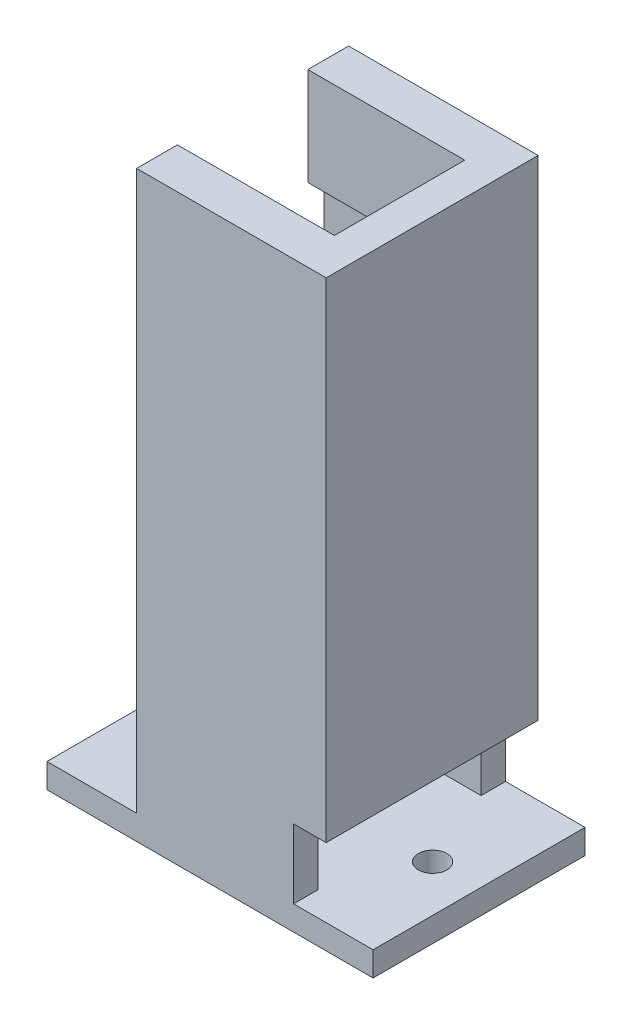
SolidWorks part; units mm, degrees
ref_plane "Front Plane" through (0, 0, 0) normal (0, 0, 1) x (1, 0, 0)
ref_plane "Top Plane" through (0, 0, 0) normal (0, 1, 0) x (1, 0, 0)
ref_plane "Right Plane" through (0, 0, 0) normal (1, 0, 0) x (0, 0, -1)
sketch "Sketch1" plane through (0, 0, 0) normal (0, 1, 0) x (1, 0, 0)
  line L1 (-20, 13) -> (20, 13)
  line L2 (-20, 13) -> (-20, -13)
  line L3 (-20, -13) -> (20, -13)
  line L4 (20, 13) -> (20, -13)
  dimension "D1" = 40
  dimension "D2" = 26
  dimension "D3" = 13
  dimension "D4" = 20
extrude "Boss-Extrude1" add sketch "Sketch1" along normal blind 3 contours L1 L4 L3 L2
sketch "Sketch2" plane through (0, 3, 0) normal (0, 1, 0) x (1, 0, 0)
  line L0 (20, 0) -> (14.3, 0) construction
  line L1 (20, 13) -> (20, -13) construction
  line L2 (0, 13) -> (0, -13) construction
  line L3 (-20, 13) -> (20, 13) construction
  line L4 (-20, -13) -> (20, -13) construction
  line L5 (-20, 0) -> (-14.3, 0) construction
  circle A0 centre (14.3, 0) radius 1.75
  circle A1 centre (-14.3, 0) radius 1.75
extrude "Cut-Extrude1" cut sketch "Sketch2" against normal blind 3
sketch "Sketch3" plane through (0, 3, 0) normal (0, 1, 0) x (1, 0, 0)
  line L0 (-20, 13) -> (20, 13) construction
  line L1 (0, 0) -> (50000, 0) construction
  line L2 (0, 0) -> (0, 50000) construction
  line L3 (-9, -10) -> (10.25, -10)
  line L4 (-9, 13) -> (10.25, 13)
  line L5 (-9, 13) -> (-9, 10)
  line L6 (-9, 10) -> (10.25, 10)
  line L7 (10.25, 13) -> (10.25, 10)
  line L8 (10.25, -13) -> (10.25, -10)
  line L9 (-9, -13) -> (10.25, -13)
  line L10 (-9, -13) -> (-9, -10)
  line L11 (0, 0) -> (10.5, 0) construction
  point P0 (-9, 13)
  point P9 (9, 13)
  dimension "D1" = 11
  dimension "D2" = 3
  dimension "D3" = 19.25
extrude "Boss-Extrude2" add sketch "Sketch3" along normal blind 56.5
sketch "Sketch5" plane through (0, 59.5, 0) normal (0, 1, 0) x (1, 0, 0)
  line L0 (-9, 13) -> (-9, -13) construction
  line L1 (-9, -8) -> (-9, 8) construction
  line L2 (-9, 0) -> (49991, 0) construction
  line L3 (-9, 13) -> (10.25, 13)
  line L4 (-9, 13) -> (-9, 8)
  line L5 (-9, 8) -> (10.25, 8)
  line L6 (10.25, 13) -> (10.25, 8)
  line L11 (-9, -8) -> (10.25, -8)
  line L12 (10.25, -13) -> (10.25, -8)
  line L13 (-9, -13) -> (10.25, -13)
  line L14 (-9, -13) -> (-9, -8)
  point P7 (-9, 0)
  dimension "D1" = 26
  dimension "D2" = 19.25
extrude "Boss-Extrude4" add sketch "Sketch5" along normal blind 12
sketch "Sketch6" plane through (0, 3, 0) normal (0, 1, 0) x (1, 0, 0)
  circle A0 centre (0, 0) radius 2.5
extrude "Cut-Extrude2" cut sketch "Sketch6" against normal blind 15
sketch "Sketch7" plane through (10.25, 0, 0) normal (1, 0, 0) x (0, 0, -1)
  line L0 (-13, 3) -> (-13, 11.5) construction
  line L1 (-13, 71.5) -> (-13, 3) construction
  line L3 (-13, 11.5) -> (13, 11.5)
  line L4 (-13, 11.5) -> (-13, 71.5)
  line L5 (-13, 71.5) -> (13, 71.5)
  line L6 (13, 11.5) -> (13, 71.5)
extrude "Boss-Extrude5" add sketch "Sketch7" along normal blind 4
